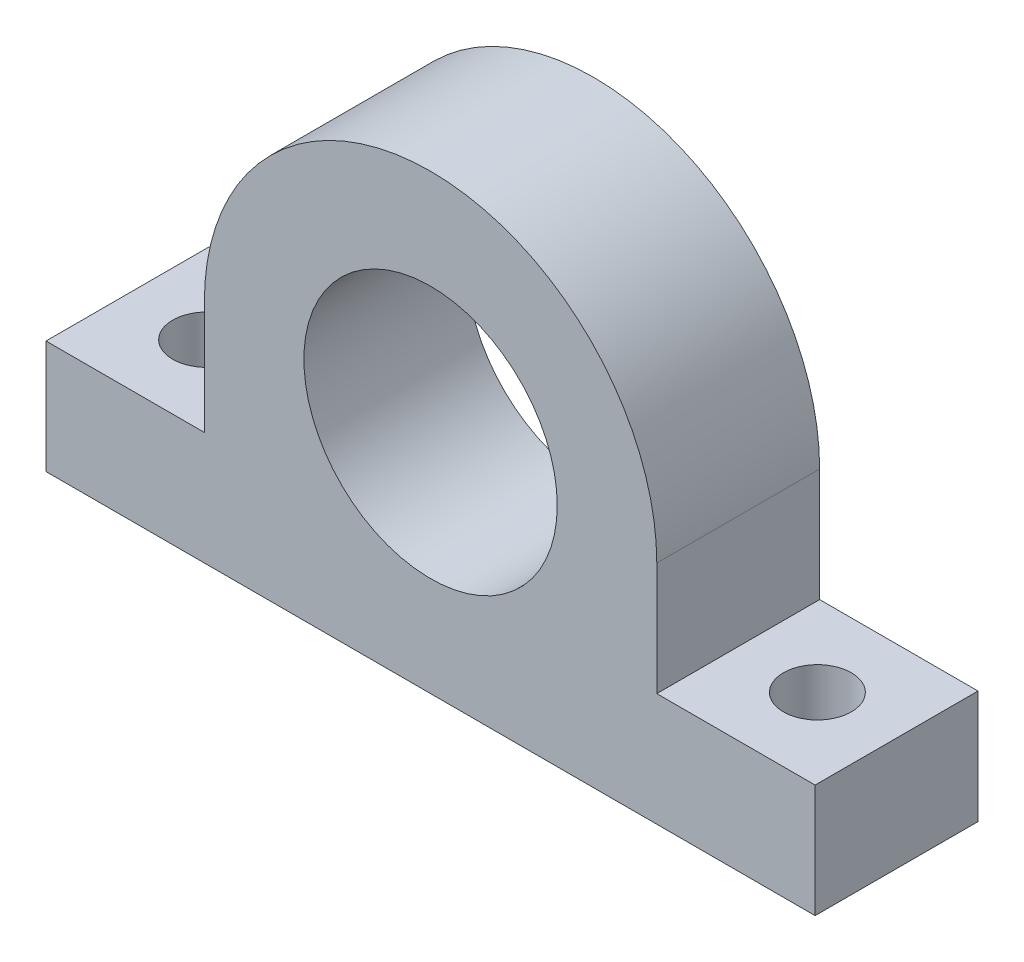
SolidWorks part; units mm, degrees
ref_plane "Alzado" through (0, 0, 0) normal (0, 0, 1) x (1, 0, 0)
ref_plane "Planta" through (0, 0, 0) normal (0, 1, 0) x (1, 0, 0)
ref_plane "Vista lateral" through (0, 0, 0) normal (1, 0, 0) x (0, 0, -1)
sketch "Sketch1" plane through (0, 0, 0) normal (0, 0, 1) x (1, 0, 0)
  line L0 (10, 0) -> (17, 0)
  line L1 (17, 0) -> (17, -5)
  line L2 (17, -5) -> (-17, -5)
  line L3 (-17, -5) -> (-17, 0)
  line L4 (-17, 0) -> (-10, 0)
  line L5 (-10, 0) -> (-10, 5)
  line L6 (10, 5) -> (10, 0)
  arc A1 (-10, 5) -> (10, 5) centre (0, 5) cw
  circle A2 centre (0, 5) radius 5.6
  dimension "D2" = 10
  dimension "D5" = 11.2
  dimension "D1" = 5
  dimension "D3" = 7
  dimension "D4" = 5
extrude "Boss-Extrude1" add sketch "Sketch1" along normal blind 7.2
sketch "Sketch2" plane through (0, 0, 0) normal (0, 1, 0) x (1, 0, 0)
  line L0 (0, 0) -> (0, -50000) construction
  line L1 (10, 0) -> (-10, 0) construction
  line L2 (17, -7.2) -> (17, 0) construction
  line L3 (17, -7.2) -> (10, -7.2) construction
  circle A0 centre (13.5, -3.6) radius 1.5
  circle A1 centre (-13.5, -3.6) radius 1.5
  point P6 (0, 0)
  point P10 (17, -3.6)
  point P13 (13.5, -7.2)
  dimension "D1" = 3
extrude "Cut-Extrude1" cut sketch "Sketch2" against normal through all
